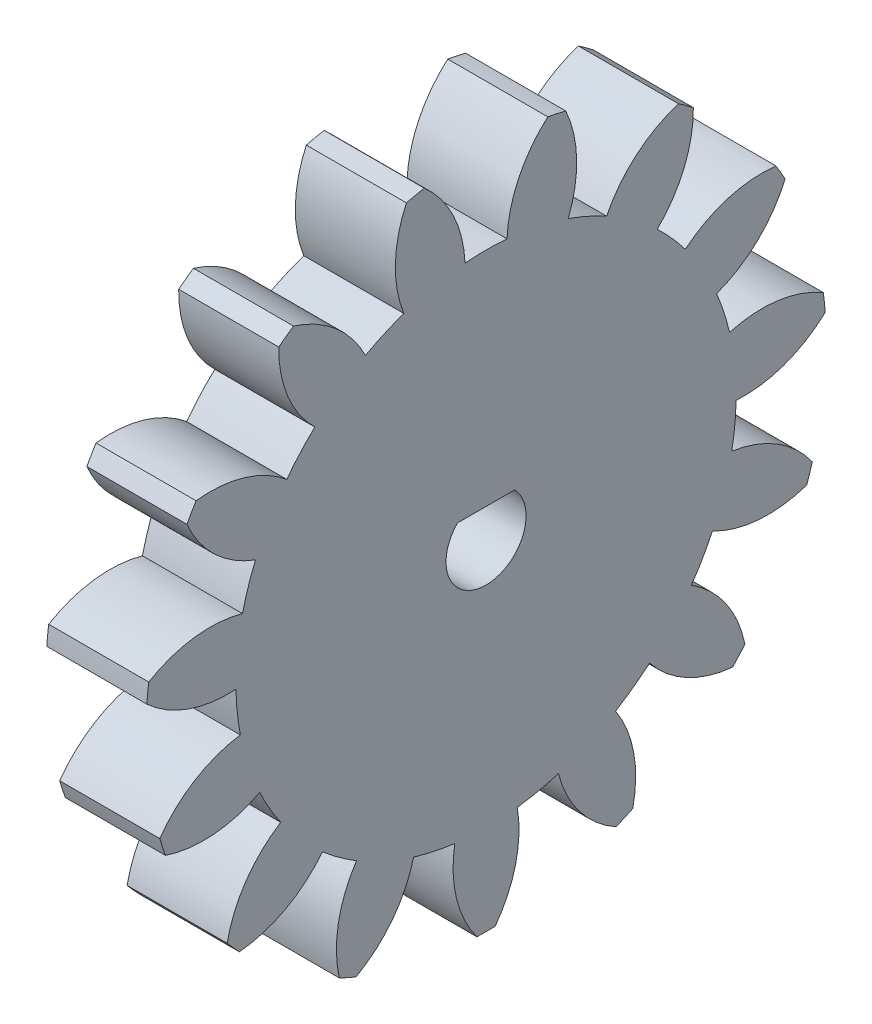
SolidWorks part; units mm, degrees
ref_plane "Plane1" through (0, 0, 0) normal (0, 0, 1) x (1, 0, 0)
ref_plane "Plane2" through (0, 0, 0) normal (0, 1, 0) x (1, 0, 0)
ref_plane "Plane3" through (0, 0, 0) normal (1, 0, 0) x (0, 0, -1)
sketch "HoldingSke" plane through (0, 0, 0) normal (0, 1, 0) x (1, 0, 0)
  line L0 (0, 0) -> (0.483, -0.1294)
  line L1 (-15, 0) -> (100, 0) construction
  line L2 (0, 0) -> (-2.1039, 2.3779)
  line L3 (0, 0) -> (-11.863, 4.5341)
  line L4 (0, 0) -> (8.3417, 2.2352)
  line L5 (0, 0) -> (-46.8476, -17.4728)
  line L6 (0, 0) -> (-4.1448, -2.7965)
  line L7 (-2.1039, 2.3779) -> (8.6586, 51.2059)
  line L8 (-76.2, 54.61) -> (-75.5, 54.61)
  line L9 (-71.009, 38.7566) -> (-53.1078, 45.2721)
  line L10 (-76.2, 71.12) -> (104.1128, 71.12)
  line L11 (0, 0) -> (-5, 0)
  line L12 (-76.2, 101.6) -> (-76.133, 101.6)
  line L13 (24.9733, 27.94) -> (52.9518, 28.4284)
  line L14 (24.9733, 27.94) -> (24.9743, 27.94)
  line L15 (24.9733, 27.94) -> (100.4006, 29.5858)
  line L16 (-63.627, -2) -> (-12.827, -2)
  circle A0 centre (0, 0) radius 2
  circle A1 centre (0, 0) radius 12.499
  circle A2 centre (0, 0) radius 37.5
  circle A3 centre (0, 0) radius 2
  dimension "MHD" = 24.998
  dimension "Hub_dia" = 75
  dimension "Bore" = 4
  dimension "MBD" = 4
  dimension "Num_teeth" = 15
  dimension "Pitch" = 0.5
  dimension "Overall_len" = 50
  dimension "Show_teeth" = 15
  dimension "Thickness" = 5
  dimension "OAL" = 50.0001
  dimension "T_dim" = 0.7
  dimension "Ap" = 20
  dimension "H" = 19.05
  dimension "Pitch_radius" = 180.3128
  dimension "Width" = 5
  dimension "Backlash" = 0.067
  dimension "Addendum_fac" = 1
  dimension "Dedendum_fac" = 1.25
  dimension "Clearance_fac" = 0.25
  dimension "Dedendum_add" = 0.001
  dimension "Module" = 2
sketch "BasProSke" plane through (0, 0, 0) normal (0, 1, 0) x (1, 0, 0)
  line L0 (-10, 0) -> (60, 0) construction
  line L1 (0, 0) -> (0, 17)
  line L2 (0, 0) -> (5, 0)
  line L3 (5, 0) -> (5, 17)
  line L4 (5, 17) -> (0, 17)
  dimension "Thickness" = 5
  dimension "Diameter" = 34
revolve "Base-Revolve" add sketch "BasProSke" angle 360 about L0
sketch "TooCutSke" plane through (0, 0, 0) normal (1, 0, 0) x (0, 0, -1)
  line L1 (0, 0) -> (0, 107) construction
  line L2 (0, 0) -> (-1.6851, 14.905) construction
  line L3 (0, 0) -> (-6.2081, 29.2069) construction
  line L4 (-1.6851, 14.905) -> (-3.1041, 14.6034) construction
  arc A0 (1.0501, 12.4548) -> (-1.0501, 12.4548) centre (0, 0) ccw
  arc A1 (3.1109, 16.7388) -> (-3.1109, 16.7388) centre (0, 0) ccw
  circle A2 centre (0, 0) radius 15 construction
  circle A3 centre (0, 0) radius 14.0954 construction
  arc A4 (-1.0501, 12.4548) -> (-3.1109, 16.7388) centre (-7.045, 12.2085) ccw
  arc A5 (3.1109, 16.7388) -> (1.0501, 12.4548) centre (7.045, 12.2085) ccw
  dimension "Root_dia" = 24.998
  dimension "Overcut_dia" = 34.0508
  dimension "Pitch_dia" = 30
  dimension "Base_dia" = 28.1908
  dimension "Flank_rad" = 6
  dimension "Half_ang" = 12
  dimension "Half_CT" = 1.4507
extrude "ToothCut" cut sketch "TooCutSke" along normal through all
fillet "Breaks" [suppressed] radius 0.04
fillet "RootFillets" [suppressed] radius 0.501
pattern_circular "TeethCuts" count 15 every 24 about axis through (-10, 0, 0) along (1, 0, 0) of "ToothCut", "RootFillets", "Breaks"
sketch "HubNeaOneSke" plane through (0, 0, 0) normal (-1, 0, 0) x (0, 0, 1)
  circle A0 centre (0, 0) radius 12.499
  dimension "Diameter" = 24.998
extrude "HubNearOne" [suppressed] add sketch "HubNeaOneSke" along normal blind 45.0001
sketch "HubNeaBotSke" plane through (0, 0, 0) normal (-1, 0, 0) x (0, 0, 1)
  circle A0 centre (0, 0) radius 12.499
  dimension "Diameter" = 24.998
extrude "HubNearBoth" [suppressed] add sketch "HubNeaBotSke" along normal blind 22.5
ref_plane "FarPln" through (5, 0, 0) normal (1, 0, 0) x (0, 0, -1)
sketch "HubFarSke" plane through (5, 0, 0) normal (1, 0, 0) x (0, 0, -1)
  circle A0 centre (0, 0) radius 12.499
  dimension "Diameter" = 24.998
extrude "HubFar" [suppressed] add sketch "HubFarSke" along normal blind 22.5
sketch "BorSke" plane through (0, 0, 0) normal (1, 0, 0) x (0, 0, -1)
  circle A0 centre (0, 0) radius 2
  dimension "Diameter" = 4
extrude "Bore" cut sketch "BorSke" along normal mid plane 100.0001
sketch "KeySke" plane through (0, 0, 0) normal (1, 0, 0) x (0, 0, -1)
  line L0 (-0.8, 0) -> (-0.8, 2.7)
  line L1 (-0.8, 2.7) -> (0.8, 2.7)
  line L2 (0.8, 2.7) -> (0.8, 0)
  line L3 (0, 0) -> (0, 34) construction
  line L4 (-0.8, 0) -> (0.8, 0)
  dimension "Offset" = 2.7
  dimension "Width" = 1.6
extrude "Keyway" [suppressed] cut sketch "KeySke" along normal mid plane 100.0001
pattern_circular "Keyway2" [suppressed] count 2 every 90 about axis through (-10, 0, 0) along (1, 0, 0)
sketch "Sketch1" plane through (5, 0, 0) normal (1, 0, 0) x (0, 0, -1)
  line L0 (-1.4283, 1.4) -> (1.4283, 1.4)
  circle A0 centre (0, 0) radius 2 construction
  arc A1 (1.4283, 1.4) -> (-1.4283, 1.4) centre (0, 0) ccw
  dimension "D1" = 1.4
extrude "Boss-Extrude1" add sketch "Sketch1" against normal blind 5
equation "' \"Module@HoldingSke\" = 6.35"
equation "' \"Num_teeth@HoldingSke\" = 12"
equation "' \"Ap@HoldingSke\" =  20"
equation "' \"Ap@HoldingSke\" = 20"
equation "' \"Width@HoldingSke\" = 0.5 * 25.4"
equation "' \"Hub_dia@HoldingSke\"= 1 * 25.4"
equation "' \"Hub_dia@HoldingSke\" = 1 * 25.4"
equation "' \"Overall_len@HoldingSke\" = 1.0 * 25.4"
equation "' \"Bore@HoldingSke\" = 0.75 * 25.4"
equation "' \"T_dim@HoldingSke\" = 0.1 * 25.4"
equation "' \"Width@KeySke\" = 0.25 * 25.4"
equation "' \"Show_teeth@HoldingSke\" = 13"
equation "' \"Backlash@HoldingSke\" = 0.009 * 25.4"
equation "' \"Addendum_fac@HoldingSke\" = 1.0"
equation "' \"Dedendum_fac@HoldingSke\" = 1.25"
equation "' \"Dedendum_add@HoldingSke\" = 0.00005 * 25.4"
equation "' \"Clearance_fac@HoldingSke\" = 0.25"
equation "\"Pitch@HoldingSke\" = 1 / \"Module@HoldingSke\""
equation "\"Overcut_dia@TooCutSke\" = (\"Num_teeth@HoldingSke\" + 2 * \"Addendum_fac@HoldingSke\") / \"Pitch@HoldingSke\" + 0.002 * 25.4"
equation "\"Pitch_dia@TooCutSke\" = \"Num_teeth@HoldingSke\" / \"Pitch@HoldingSke\""
equation "\"Base_dia@TooCutSke\" = \"Num_teeth@HoldingSke\" / \"Pitch@HoldingSke\" * cos((\"Ap@HoldingSke\"  * 3.14159265 / 180))"
equation "\"Root_dia@TooCutSke\" = (\"Num_teeth@HoldingSke\" + 2) / \"Pitch@HoldingSke\" - 2 * (\"Addendum_fac@HoldingSke\" + \"Dedendum_fac@HoldingSke\") / \"Pitch@HoldingSke\" - \"Dedendum_add@HoldingSke\" * 2"
equation "\"Half_ang@TooCutSke\" = 180 / \"Num_teeth@HoldingSke\""
equation "\"Half_CT@TooCutSke\" = \"Num_teeth@HoldingSke\" / \"Pitch@HoldingSke\" * sin((3.14159265 / 2 / \"Num_teeth@HoldingSke\")) / 2 - 7 * \"Backlash@HoldingSke\" / 4"
equation "\"Flank_rad@TooCutSke\" = \"Num_teeth@HoldingSke\" / \"Pitch@HoldingSke\" / 5"
equation "\"Radius@RootFillets\" = \"Clearance_fac@HoldingSke\" / \"Pitch@HoldingSke\" + \"Dedendum_add@HoldingSke\""
equation "\"Break_rad@Breaks\" = 0.02 / \"Pitch@HoldingSke\""
equation "\"Thickness@HoldingSke\" = \"Width@HoldingSke\""
equation "\"OAL@HoldingSke\" = \"Thickness@HoldingSke\""
equation "\"MHD@HoldingSke\" = (\"Num_teeth@HoldingSke\" + 2) / \"Pitch@HoldingSke\" - 2 * (\"Addendum_fac@HoldingSke\" + \"Dedendum_fac@HoldingSke\")  / \"Pitch@HoldingSke\" - \"Dedendum_add@HoldingSke\" * 2"
equation "\"MBD@HoldingSke\" = (\"Num_teeth@HoldingSke\" + 2) / \"Pitch@HoldingSke\" - 2 * (\"Addendum_fac@HoldingSke\" + \"Dedendum_fac@HoldingSke\")  / \"Pitch@HoldingSke\" - \"Dedendum_add@HoldingSke\" * 2 - 0.002 * 25.4"
equation "\"MHD@HoldingSke\" = ((sgn( \"MHD@HoldingSke\" - \"Hub_dia@HoldingSke\" )-1)*( \"MHD@HoldingSke\" - \"Hub_dia@HoldingSke\" ))/-2+ \"Hub_dia@HoldingSke\""
equation "\"MBD@HoldingSke\" = ((sgn( \"MBD@HoldingSke\" - \"Bore@HoldingSke\" )-1)*( \"MBD@HoldingSke\" - \"Bore@HoldingSke\" ))/-2+ \"Bore@HoldingSke\""
equation "\"OAL@HoldingSke\" = ((sgn( \"OAL@HoldingSke\" - \"Overall_len@HoldingSke\" )+1)*( \"OAL@HoldingSke\" - \"Overall_len@HoldingSke\" ))/2 + \"Overall_len@HoldingSke\" + 0.000002 * 25.4"
equation "\"Num_teeth@TeethCuts\" = int( \"Show_teeth@HoldingSke\" ) + 1"
equation "\"Num_teeth@TeethCuts\" = ((sgn( \"Num_teeth@TeethCuts\" - \"Num_teeth@HoldingSke\" )-1)*( \"Num_teeth@TeethCuts\" - \"Num_teeth@HoldingSke\" ))/-2+ \"Num_teeth@HoldingSke\""
equation "\"Num_teeth@TeethCuts\" = ((sgn( \"Num_teeth@TeethCuts\" - 2.0)+1)*( \"Num_teeth@TeethCuts\" - 2.0))/2 +2.0"
equation "\"Angle@TeethCuts\" = 360.0 / \"Num_teeth@HoldingSke\""
equation "\"Diameter@BasProSke\" = (\"Num_teeth@HoldingSke\" + 2 * \"Addendum_fac@HoldingSke\") / \"Pitch@HoldingSke\""
equation "\"Thickness@BasProSke\"  = \"Thickness@HoldingSke\""
equation "' \"Fillet_rad@BasProSke\" =  \"Thickness@HoldingSke\" * 0.05"
equation "' \"Fillet_rad@BasProSke\" = \"Thickness@HoldingSke\" * 0.05"
equation "\"MHD@HoldingSke\" = ((sgn( \"MHD@HoldingSke\" - \"Root_dia@TooCutSke\" )-1)*( \"MHD@HoldingSke\" - \"Root_dia@TooCutSke\" ))/-2+ \"Root_dia@TooCutSke\""
equation "\"Diameter@HubNeaOneSke\" = \"MHD@HoldingSke\""
equation "\"Length@HubNearOne\" = \"OAL@HoldingSke\" - \"Thickness@BasProSke\""
equation "\"Diameter@HubNeaBotSke\" = \"MHD@HoldingSke\""
equation "\"Length@HubNearBoth\" = ( \"OAL@HoldingSke\" - \"Thickness@BasProSke\" ) / 2.0"
equation "\"Thickness@FarPln\" = \"Thickness@BasProSke\""
equation "\"Diameter@HubFarSke\" = \"MHD@HoldingSke\""
equation "\"Length@HubFar\" = ( \"OAL@HoldingSke\" - \"Thickness@BasProSke\" ) / 2.0"
equation "\"Diameter@BorSke\" = \"MBD@HoldingSke\""
equation "\"D1@Bore\" = \"OAL@HoldingSke\" * 2.0"
equation "\"D1@Keyway\" = \"OAL@HoldingSke\" * 2.0"
equation "\"Offset@KeySke\" = \"T_dim@HoldingSke\" + \"MBD@HoldingSke\" / 2.0"
